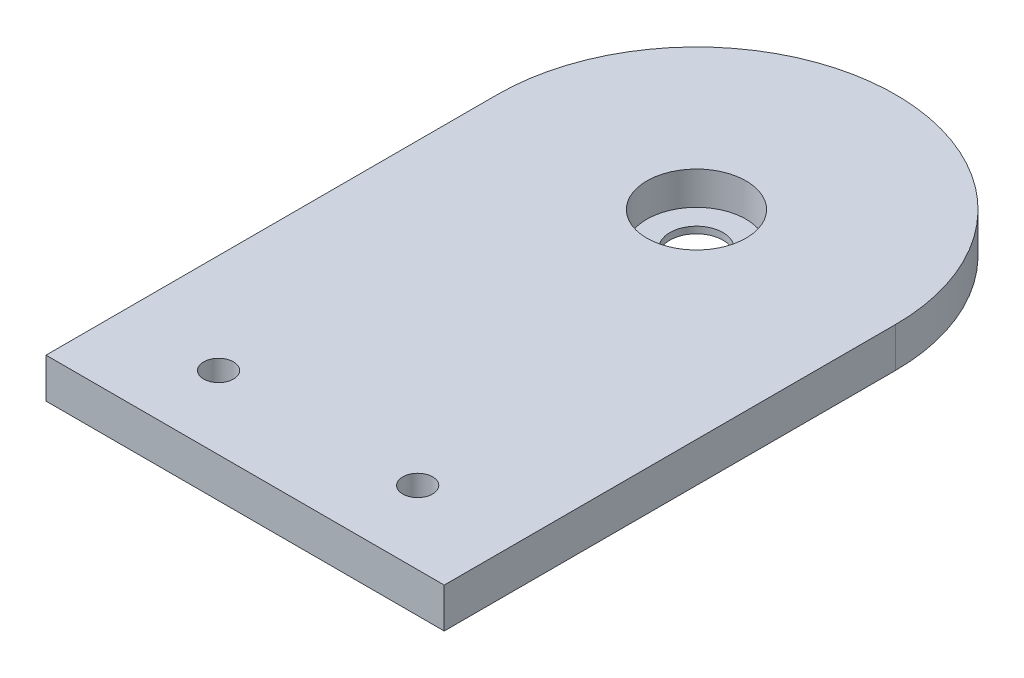
SolidWorks part; units mm, degrees
material "Aleación 6061"
ref_plane "Alzado" through (0, 0, 0) normal (0, 0, 1) x (1, 0, 0)
ref_plane "Planta" through (0, 0, 0) normal (0, 1, 0) x (1, 0, 0)
ref_plane "Vista lateral" through (0, 0, 0) normal (1, 0, 0) x (0, 0, -1)
sketch "Sk_Placa" plane through (0, 0, 0) normal (0, 1, 0) x (1, 0, 0)
  line L1 (-30, -379) -> (30, -379)
  line L2 (-30, -379) -> (-30, -330)
  line L3 (-30, -330) -> (30, -330)
  line L4 (30, -379) -> (30, -330)
  line L5 (-30, -379) -> (30, -330) construction
  line L6 (-30, -330) -> (30, -379) construction
  point P0 (0, -354.5)
  dimension "D1" = 60
  dimension "D2" = 49
  dimension "D3" = 354.5
extrude "Placa" add sketch "Sk_Placa" along normal blind 6 from offset 65.75
sketch "Sk_Extremo" plane through (0, 0, 0) normal (0, 1, 0) x (1, 0, 0)
  circle A0 centre (0, -330) radius 30
  dimension "D1" = 60
  dimension "D2" = 330
extrude "Extremo" add sketch "Sk_Extremo" along normal blind 6 from offset 65.75
sketch "Sk_Alojamiento_696ZZ" plane through (0, 0, 0) normal (0, 1, 0) x (1, 0, 0)
  circle A0 centre (0, -330) radius 7.475
  dimension "D1" = 14.95
  dimension "D2" = 330
extrude "Alojamiento_696ZZ" cut sketch "Sk_Alojamiento_696ZZ" along normal blind 5 from offset 64.75
sketch "Sk_Paso_extractor" plane through (0, 0, 0) normal (0, 1, 0) x (1, 0, 0)
  circle A0 centre (0, -330) radius 4
  dimension "D1" = 8
  dimension "D2" = 330
extrude "Paso_extractor" cut sketch "Sk_Paso_extractor" along normal blind 1 from offset 65.75
sketch "Sk_Extension_pestanas" plane through (0, 0, 0) normal (0, 1, 0) x (1, 0, 0)
  line L1 (-30, -398) -> (30, -398)
  line L2 (-30, -398) -> (-30, -379)
  line L3 (-30, -379) -> (30, -379)
  line L4 (30, -398) -> (30, -379)
  line L5 (-30, -398) -> (30, -379) construction
  line L6 (-30, -379) -> (30, -398) construction
  point P0 (0, -388.5)
  dimension "D1" = 60
  dimension "D2" = 19
  dimension "D3" = 388.5
extrude "Extension_pestanas" add sketch "Sk_Extension_pestanas" along normal blind 6 from offset 65.75
sketch "Sk_Pasantes_M4_repisa" plane through (0, 0, 0) normal (0, 1, 0) x (1, 0, 0)
  circle A0 centre (-15, -387) radius 2.25
  circle A1 centre (15, -387) radius 2.25
  dimension "D1" = 4.5
  dimension "D4" = 4.5
  dimension "D2" = 15
  dimension "D3" = 387
  dimension "D5" = 15
  dimension "D6" = 387
extrude "Pasantes_M4_repisa" cut sketch "Sk_Pasantes_M4_repisa" along normal blind 6 from offset 65.75
